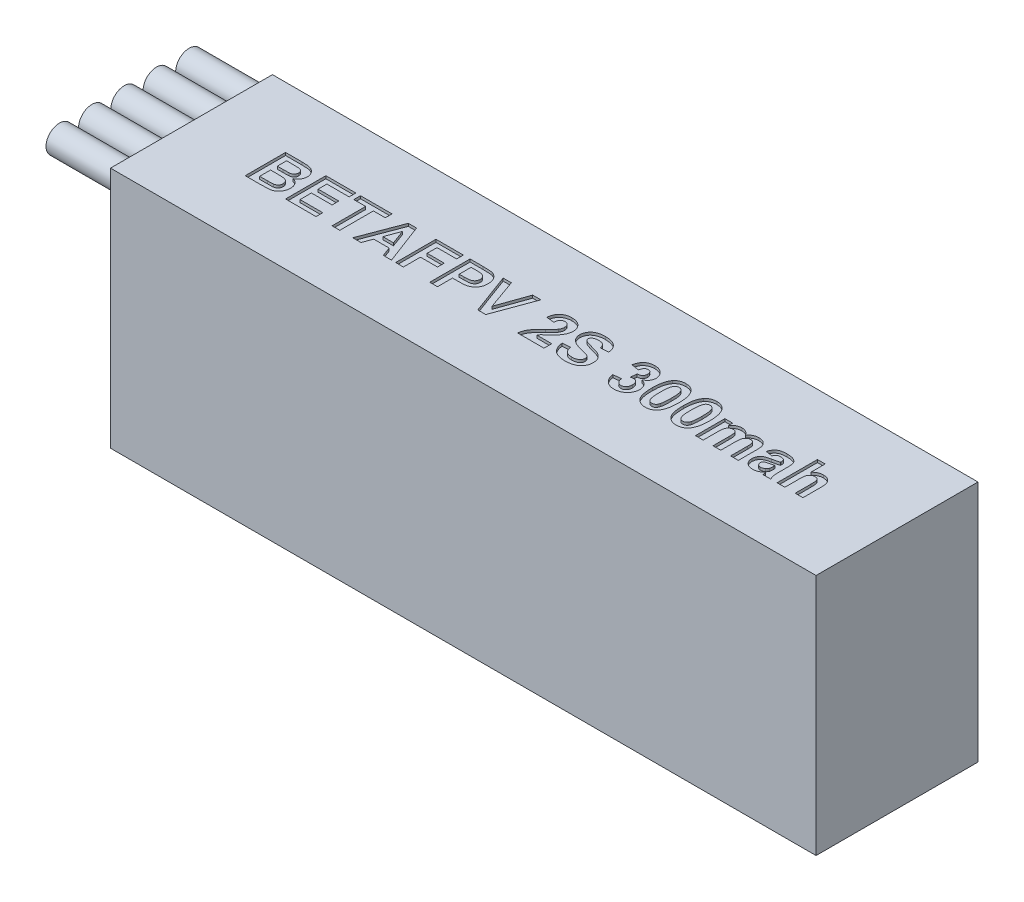
SolidWorks part; units mm, degrees
ref_plane "Front Plane" through (0, 0, 0) normal (0, 0, 1) x (1, 0, 0)
ref_plane "Top Plane" through (0, 0, 0) normal (0, 1, 0) x (1, 0, 0)
ref_plane "Right Plane" through (0, 0, 0) normal (1, 0, 0) x (0, 0, -1)
sketch "Sketch1" plane through (0, 0, 0) normal (0, 0, 1) x (1, 0, 0)
  line L1 (-26.25, 9.025) -> (26.25, 9.025)
  line L2 (-26.25, 9.025) -> (-26.25, -9.025)
  line L3 (-26.25, -9.025) -> (26.25, -9.025)
  line L4 (26.25, 9.025) -> (26.25, -9.025)
  line L5 (-26.25, 9.025) -> (26.25, -9.025) construction
  line L6 (-26.25, -9.025) -> (26.25, 9.025) construction
  point P0 (0, 0)
  dimension "D1" = 52.5
  dimension "D2" = 18.05
extrude "Boss-Extrude1" add sketch "Sketch1" along normal mid plane 12.05
sketch "Sketch3" plane through (-26.25, 0, 0) normal (-1, 0, 0) x (0, 0, 1)
  line L0 (-6.025, 7.825) -> (6.025, 7.825) construction
  line L1 (0, 0) -> (0, 9.025) construction
  line L4 (-6.025, 9.025) -> (-6.025, -9.025)
  line L5 (-6.025, -9.025) -> (6.025, -9.025)
  line L6 (6.025, -9.025) -> (6.025, 9.025)
  line L7 (6.025, 9.025) -> (-6.025, 9.025)
  line L8 (-6.025, 9.025) -> (-6.025, -9.025) construction
  line L9 (-6.025, -9.025) -> (6.025, -9.025) construction
  line L10 (6.025, -9.025) -> (6.025, 9.025) construction
  line L11 (6.025, 9.025) -> (-6.025, 9.025) construction
  circle A1 centre (0, 7.825) radius 1.2 construction
  circle A2 centre (-4.825, 7.825) radius 1.2 construction
  circle A3 centre (-2.4, 7.825) radius 1.2 construction
  circle A4 centre (2.4, 7.825) radius 1.2 construction
  circle A5 centre (4.825, 7.825) radius 1.2 construction
  circle A6 centre (-4.825, 7.825) radius 1
  circle A7 centre (-2.4, 7.825) radius 1
  circle A8 centre (0, 7.825) radius 1
  circle A9 centre (2.4, 7.825) radius 1
  circle A10 centre (4.825, 7.825) radius 1
  point P15 (-2.6692, 7.825)
  dimension "D2" = 2.4
  dimension "D3" = 2.4
  dimension "D1" = 0
  dimension "D4" = 0.2
extrude "Boss-Extrude6" add sketch "Sketch3" along normal blind 5
sketch "Sketch4" plane through (0, 9.025, 0) normal (0, 1, 0) x (1, 0, 0)
  line L0 (-26.25, 0) -> (26.25, 0) construction
  line L1 (-26.25, -6.025) -> (-26.25, 6.025) construction
  line L2 (26.25, -6.025) -> (26.25, 6.025) construction
  line L3 (-26.25, -1.5) -> (26.25, -1.5) construction
  text T0 "BETAFPV 2S 300mah" font "Arial" height 3
  dimension "D1" = 1.5
extrude "Cut-Extrude1" cut sketch "Sketch4" against normal blind 0.2
sketch "Sketch5" plane through (0, 0, 0) normal (0, 0, 1) x (1, 0, 0)
  point P0 (0, 0)
